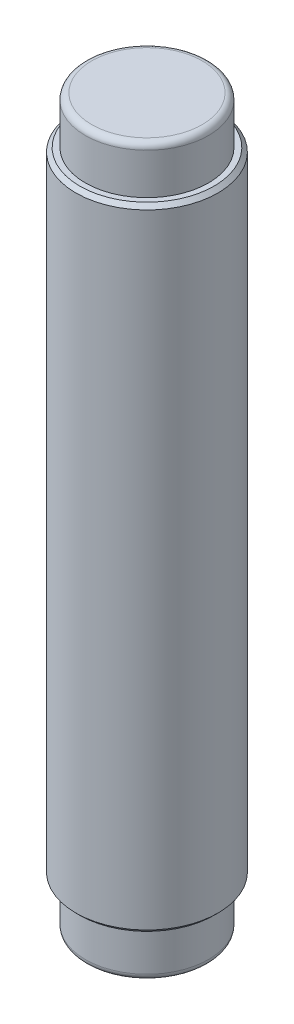
SolidWorks part; units mm, degrees
ref_plane "Front Plane" through (0, 0, 0) normal (0, 0, 1) x (1, 0, 0)
ref_plane "Top Plane" through (0, 0, 0) normal (0, 1, 0) x (1, 0, 0)
ref_plane "Right Plane" through (0, 0, 0) normal (1, 0, 0) x (0, 0, -1)
sketch "Sketch1" plane through (0, 0, 0) normal (0, 1, 0) x (1, 0, 0)
  circle A0 centre (0, 0) radius 3.9
extrude "Boss-Extrude1" add sketch "Sketch1" along normal blind 46
fillet "Fillet5" radius 0.4 2 edges at (0, 0, 3.9) (0, 46, 3.9)
ref_plane "Plane1" through (0, 23, 0) normal (0, 1, 0) x (1, 0, 0)
sketch "Sketch2" plane through (0, 23, 0) normal (0, 1, 0) x (1, 0, 0)
  circle A0 centre (0, 0) radius 4.5
  dimension "D1" = 9
extrude "Boss-Extrude2" add sketch "Sketch2" along normal mid plane 40
chamfer "Chamfer1" distance 0.25 angle 45 2 edges at (0, 3, 4.5) (0, 43, 4.5)
